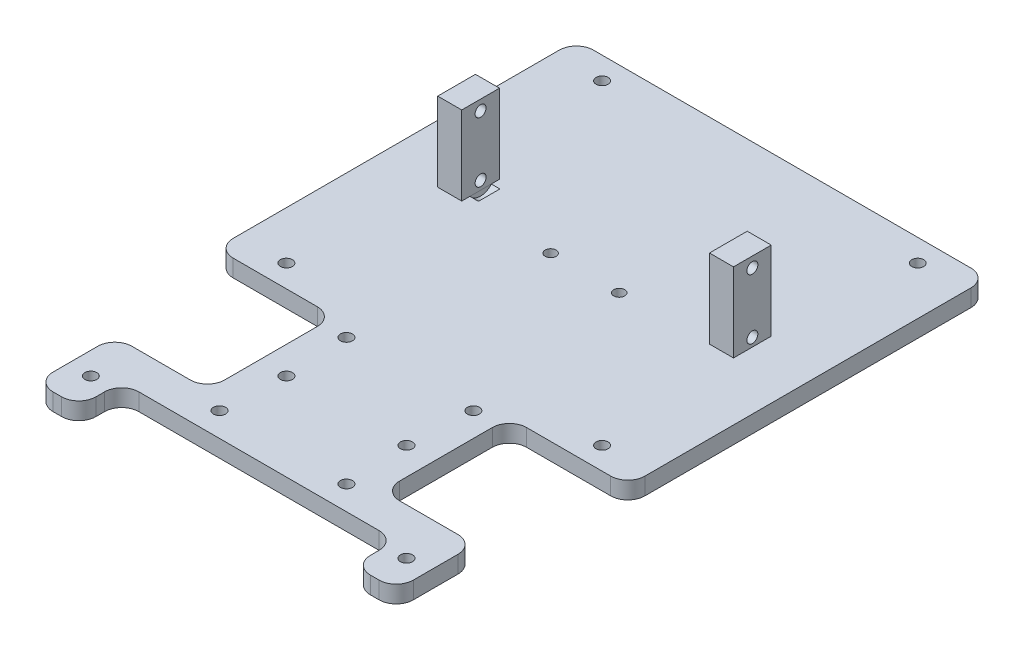
SolidWorks part; units mm, degrees
ref_plane "정면" through (0, 0, 0) normal (0, 0, 1) x (1, 0, 0)
ref_plane "윗면" through (0, 0, 0) normal (0, 1, 0) x (1, 0, 0)
ref_plane "우측면" through (0, 0, 0) normal (1, 0, 0) x (0, 0, -1)
sketch "스케치1" plane through (0, 0, 0) normal (0, 1, 0) x (1, 0, 0)
  line L0 (-52.5, -52.5) -> (-60, -52.5)
  line L1 (60, 52.5) -> (-60, 52.5)
  line L2 (60, 52.5) -> (60, -52.5)
  line L3 (60, -52.5) -> (52.5, -52.5)
  line L4 (-60, 52.5) -> (-60, -52.5)
  line L5 (60, 52.5) -> (-60, -52.5) construction
  line L6 (60, -52.5) -> (-60, 52.5) construction
  line L7 (52.5, -112.5) -> (-52.5, -112.5)
  line L8 (52.5, -112.5) -> (52.5, -52.5)
  line L10 (-52.5, -112.5) -> (-52.5, -52.5)
  line L11 (52.5, -112.5) -> (-52.5, -52.5) construction
  line L12 (52.5, -52.5) -> (-52.5, -112.5) construction
  point P0 (0, 0)
  point P6 (0, -82.5)
  dimension "D1" = 120
  dimension "D2" = 105
  dimension "D3" = 105
  dimension "D4" = 60
extrude "보스-돌출1" add sketch "스케치1" along normal blind 5
sketch "스케치2" plane through (0, 5, 0) normal (0, 1, 0) x (1, 0, 0)
  line L0 (-43.1, 29.5) -> (-43.1, -5.3) construction
  line L1 (-36.1, -4.8) -> (-43.1, -4.8)
  line L2 (-36.1, -4.8) -> (-36.1, 6.2)
  line L3 (-36.1, 6.2) -> (-43.1, 6.2)
  line L4 (-43.1, -4.8) -> (-43.1, 6.2)
  line L5 (-61.9, -0.8) -> (-43.1, -0.8) construction
  line L6 (-43.1, 2.2) -> (-61.9, 2.2) construction
  dimension "D1" = 7
  dimension "D2" = 4
  dimension "D3" = 4
extrude "보스-돌출2" add sketch "스케치2" along normal blind 23 separate body
sketch "스케치3" plane through (-36.1, 0, 0) normal (1, 0, 0) x (0, 0, -1)
  circle A0 centre (0.7, 7.5) radius 1.5 construction
  circle A1 centre (0.7, 25) radius 1.5 construction
  circle A2 centre (0.7, 25) radius 1.6
  circle A3 centre (0.7, 7.5) radius 1.6
  circle A4 centre (0.7, 7.5) radius 1.5 construction
  circle A5 centre (0.7, 25) radius 1.5 construction
  dimension "D1" = 3.2
  dimension "D2" = 3.2
extrude "컷-돌출1" cut sketch "스케치3" against normal through all
mirror "대칭 복사1" about plane through (0, 0, 0) normal (1, 0, 0) of bodies 103
sketch "스케치5" plane through (0, 5, 0) normal (0, 1, 0) x (1, 0, 0)
  circle A0 centre (-46, -46) radius 1.75 construction
  circle A1 centre (-46, 46) radius 1.75 construction
  circle A2 centre (46, 46) radius 1.75 construction
  circle A3 centre (46, -46) radius 1.75 construction
  circle A4 centre (-46, -46) radius 1.75
  circle A5 centre (-46, 46) radius 1.75
  circle A6 centre (46, 46) radius 1.75
  circle A7 centre (46, -46) radius 1.75
extrude "메인보드 홀" cut sketch "스케치5" against normal through all
sketch "Sketch2" plane through (36.1, 0, 0) normal (-1, 0, 0) x (0, 0, 1)
  circle A0 centre (-0.7, 7.5) radius 4
  dimension "D1" = 8
extrude "Cut-Extrude1" cut sketch "Sketch2" along normal blind 2.5
sketch "Sketch3" plane through (-36.1, 0, 0) normal (1, 0, 0) x (0, 0, -1)
  circle A0 centre (0.7, 7.5) radius 4
  dimension "D1" = 8
extrude "Cut-Extrude2" cut sketch "Sketch3" along normal blind 2.5
sketch "Sketch4" plane through (0, 5, 0) normal (0, 1, 0) x (1, 0, 0)
  circle A0 centre (10, -5) radius 1.5 construction
  circle A1 centre (-10, -5) radius 1.5 construction
  circle A2 centre (10, -5) radius 1.5 construction
  circle A3 centre (-10, -5) radius 1.5 construction
  circle A4 centre (-10, -5) radius 1.6
  circle A5 centre (10, -5) radius 1.6
  dimension "D1" = 3.2
  dimension "D2" = 3.2
extrude "배터리홀더 홀" cut sketch "Sketch4" against normal through all and the other way through all
sketch "Sketch6" plane through (0, 5, 0) normal (0, 1, 0) x (1, 0, 0)
  line L1 (-18.5, -93) -> (18.5, -93) construction
  line L2 (-18.5, -93) -> (-18.5, -56) construction
  line L3 (-18.5, -56) -> (18.5, -56) construction
  line L4 (18.5, -93) -> (18.5, -56) construction
  line L5 (-18.5, -93) -> (18.5, -56) construction
  line L6 (-18.5, -56) -> (18.5, -93) construction
  circle A0 centre (-46, -46) radius 1.75 construction
  circle A1 centre (-18.5, -93) radius 1.75
  circle A2 centre (-18.5, -56) radius 1.75
  circle A3 centre (18.5, -56) radius 1.75
  circle A4 centre (18.5, -93) radius 1.75
  point P0 (0, -74.5)
  dimension "D3" = 3.5
  dimension "D1" = 37
  dimension "D2" = 10
extrude "모터드라이버 홀" cut sketch "Sketch6" against normal through all
sketch "Sketch7" plane through (0, 5, 0) normal (0, 1, 0) x (1, 0, 0)
  line L0 (-46, -103) -> (46, -103) construction
  line L1 (0, -103) -> (0, 0) construction
  circle A0 centre (-46, -103) radius 1.75
  circle A1 centre (-18.5, -93) radius 1.75 construction
  circle A2 centre (46, -103) radius 1.75
  dimension "D1" = 3.5
  dimension "D3" = 3.5
  dimension "D2" = 10
  dimension "D4" = 92
extrude "센서보드 홀" cut sketch "Sketch7" against normal through all
sketch "Sketch9" plane through (0, 5, 0) normal (0, 1, 0) x (1, 0, 0)
  line L0 (-17.5, -74.5) -> (17.5, -74.5) construction
  circle A0 centre (-17.5, -74.5) radius 1.75
  circle A1 centre (17.5, -74.5) radius 1.75
  dimension "D2" = 3.5
  dimension "D1" = 35
extrude "볼캐스터 홀" cut sketch "Sketch9" against normal through all
sketch "Sketch8" plane through (0, 5, 0) normal (0, 1, 0) x (1, 0, 0)
  line L0 (-52.5, -112.5) -> (52.5, -112.5) construction
  line L1 (-40, -125) -> (40, -125)
  line L2 (-40, -125) -> (-40, -100)
  line L3 (-40, -100) -> (40, -100)
  line L4 (40, -125) -> (40, -100)
  line L5 (-40, -125) -> (40, -100) construction
  line L6 (-40, -100) -> (40, -125) construction
  point P0 (0, -112.5)
  dimension "D1" = 80
  dimension "D2" = 25
extrude "Cut-Extrude7" cut sketch "Sketch8" against normal through all
fillet "필렛1" radius 5 8 edges at (60, 2.5, -52.5) (-60, 2.5, -52.5) (52.5, 2.5, 112.5) (-52.5, 2.5, 112.5) (40, 2.5, 112.5) (-40, 2.5, 112.5) (40, 2.5, 100) (-40, 2.5, 100)
fillet "Fillet2" [suppressed] radius 5
sketch "Sketch10" plane through (0, 5, 0) normal (0, 1, 0) x (1, 0, 0)
  line L0 (0, 0) -> (0, -100) construction
  line L1 (-52.5, -52.5) -> (-25.5, -52.5)
  line L2 (-52.5, -52.5) -> (-52.5, -89.5)
  line L3 (-52.5, -89.5) -> (-25.5, -89.5)
  line L4 (-25.5, -52.5) -> (-25.5, -89.5)
  line L5 (35, -100) -> (-35, -100) construction
  line L6 (25.5, -52.5) -> (25.5, -89.5)
  line L7 (52.5, -89.5) -> (25.5, -89.5)
  line L8 (52.5, -52.5) -> (52.5, -89.5)
  line L9 (52.5, -52.5) -> (25.5, -52.5)
  dimension "D1" = 37
  dimension "D2" = 27
extrude "Cut-Extrude8" cut sketch "Sketch10" against normal through all
fillet "Fillet3" radius 5 8 edges at (60, 2.5, 52.5) (52.5, 2.5, 89.5) (25.5, 2.5, 89.5) (25.5, 2.5, 52.5) (-52.5, 2.5, 89.5) (-25.5, 2.5, 89.5) (-25.5, 2.5, 52.5) (-60, 2.5, 52.5)
